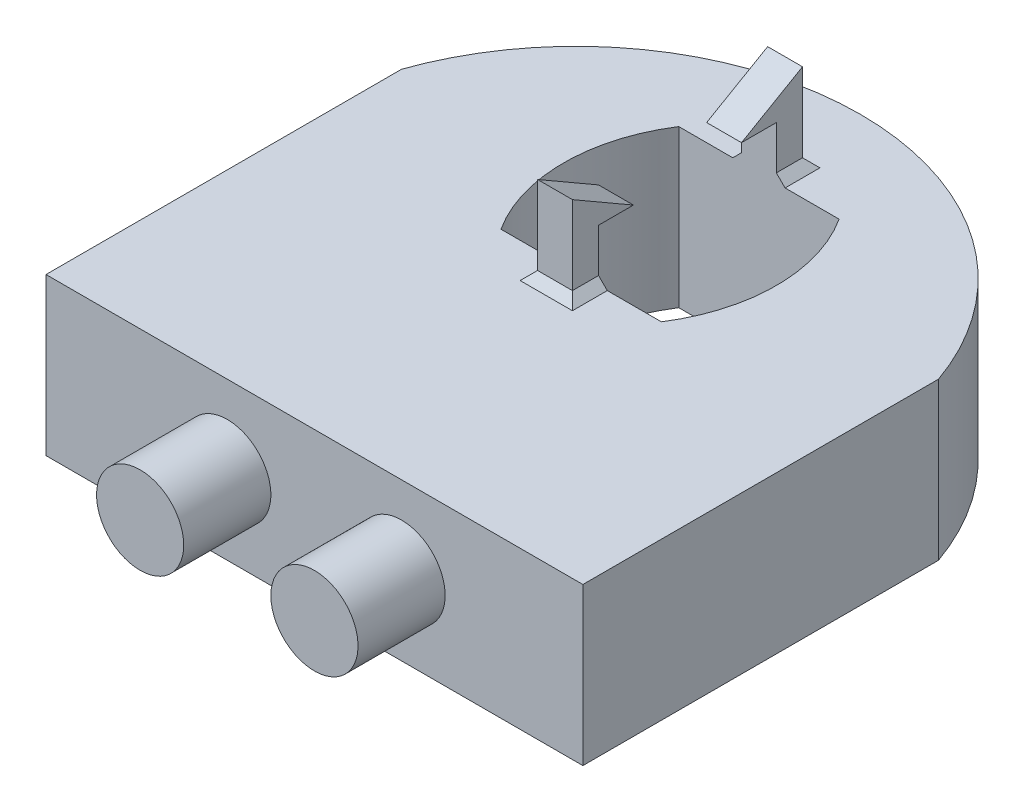
SolidWorks part; units mm, degrees
ref_plane "Front Plane" through (0, 0, 0) normal (0, 0, 1) x (1, 0, 0)
ref_plane "Top Plane" through (0, 0, 0) normal (0, 1, 0) x (1, 0, 0)
ref_plane "Right Plane" through (0, 0, 0) normal (1, 0, 0) x (0, 0, -1)
sketch "Sketch1" plane through (0, 0, 0) normal (0, 1, 0) x (1, 0, 0)
  line L0 (0, 0) -> (30.8, 40.8) construction
  line L1 (0, 0) -> (30.8, 0)
  line L2 (0, 0) -> (0, 40.8)
  line L3 (0, 40.8) -> (30.8, 40.8)
  line L4 (30.8, 0) -> (30.8, 40.8)
  line L5 (15.4, 25.5) -> (15.4, 15.3) construction
  line L6 (9.3, 15.3) -> (21.5, 15.3)
  line L7 (9.3, 15.3) -> (9.3, 25.5)
  line L8 (9.3, 25.5) -> (21.5, 25.5)
  line L9 (21.5, 15.3) -> (21.5, 25.5)
  line L10 (9.3, 15.3) -> (21.5, 25.5) construction
  line L11 (9.3, 25.5) -> (21.5, 15.3) construction
  arc A1 (0, 20.4) -> (30.8, 20.4) centre (15.4, 15) cw
  arc A2 (10.8, 25.5) -> (10.8, 15.3) centre (18.72, 20.4) ccw
  arc A3 (20, 25.5) -> (20, 15.3) centre (12.08, 20.4) cw
  point P5 (15.4, 20.4)
  dimension "D3" = 12.2
  dimension "D4" = 15
  dimension "D1" = 40.8
  dimension "D2" = 30.8
  dimension "D5" = 10.2
  dimension "D6" = 9.2
extrude "Boss-Extrude1" add sketch "Sketch1" along normal blind 9 contours A1 L2 L1 L4 L9 L6 L7 L8 | L8 A3 L9 | A2 L8 L7 | A2 L7 L6 | L9 A3 L6
ref_plane "Plane1" through (15.4, 0, 0) normal (1, 0, 0) x (0, 0, -1)
sketch "Sketch6" plane through (15.4, 0, 0) normal (1, 0, 0) x (0, 0, -1)
  line L0 (15.3, 9) -> (15.3, 12)
  line L1 (0, 9) -> (20.4, 9) construction
  line L2 (15.3, 12) -> (17.3, 12)
  line L3 (17.3, 12) -> (13.8, 14.0207)
  line L4 (13.8, 14.0207) -> (13.8, 9)
  line L5 (20.4, 9) -> (20.4, 15.4303) construction
  line L7 (20.4, 9) -> (20.4, 0) construction
  line L8 (15.3, 9) -> (13.8, 9)
  line L9 (25.5, 9) -> (25.5, 12)
  line L10 (25.5, 12) -> (23.5, 12)
  line L11 (23.5, 12) -> (27, 14.0207)
  line L12 (27, 14.0207) -> (27, 9)
  line L13 (25.5, 9) -> (27, 9)
  dimension "D1" = 1.5
  dimension "D2" = 30
  dimension "D3" = 3
  dimension "D4" = 2
extrude "Boss-Extrude4" add sketch "Sketch6" along normal mid plane 2
sketch "Sketch2" plane through (0, 0, 0) normal (0, 0, 1) x (1, 0, 0)
  line L0 (15.4, 9) -> (15.4, 0) construction
  line L1 (0, 9) -> (30.8, 9) construction
  line L2 (0, 0) -> (30.8, 0) construction
  circle A0 centre (10.4, 4.5) radius 2.5
  circle A1 centre (20.4, 4.5) radius 2.5
  point P9 (15.4, 4.5)
  dimension "D1" = 5
  dimension "D2" = 10
extrude "Boss-Extrude2" add sketch "Sketch2" along normal blind 5
chamfer "Chamfer2" distance 0.5 angle 45 6 edges at (16.4, 9, -26.25) (15.4, 9, -27) (14.4, 9, -26.25) (14.4, 9, -14.55) (15.4, 9, -13.8) (16.4, 9, -14.55)
